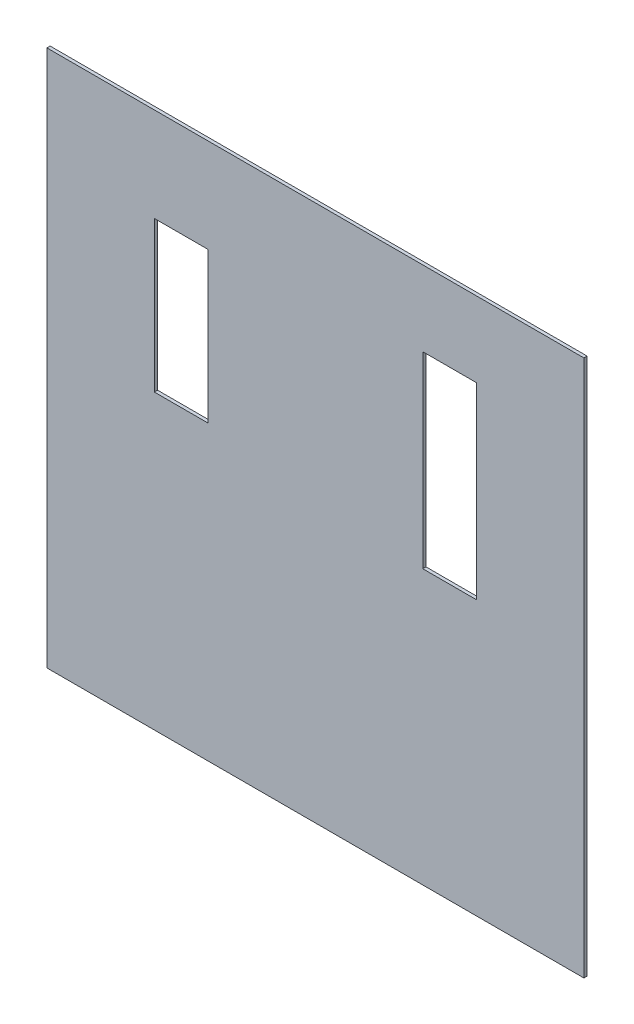
SolidWorks part; units mm, degrees
material "Custom Plastic"
ref_plane "Front Plane" through (0, 0, 0) normal (0, 0, 1) x (1, 0, 0)
ref_plane "Top Plane" through (0, 0, 0) normal (0, 1, 0) x (1, 0, 0)
ref_plane "Right Plane" through (0, 0, 0) normal (1, 0, 0) x (0, 0, -1)
sketch "Sketch1" plane through (0, 0, 0) normal (0, 0, 1) x (1, 0, 0)
  line L1 (0, 0) -> (25.4, 0)
  line L2 (0, 0) -> (0, 25.4)
  line L3 (0, 25.4) -> (25.4, 25.4)
  line L4 (25.4, 0) -> (25.4, 25.4)
  dimension "D1" = 25.4
  dimension "D2" = 25.4
extrude "Boss-Extrude1" add sketch "Sketch1" along normal blind 0.1524
sketch "Sketch2" plane through (0, 0, 0.1524) normal (0, 0, 1) x (1, 0, 0)
  line L0 (25.4, 25.4) -> (0, 25.4) construction
  line L1 (5.08, 20.955) -> (7.62, 20.955)
  line L2 (5.08, 20.955) -> (5.08, 13.843)
  line L3 (5.08, 13.843) -> (7.62, 13.843)
  line L4 (7.62, 20.955) -> (7.62, 13.843)
  line L5 (17.78, 21.844) -> (20.32, 21.844)
  line L6 (17.78, 21.844) -> (17.78, 12.954)
  line L7 (17.78, 12.954) -> (20.32, 12.954)
  line L8 (20.32, 21.844) -> (20.32, 12.954)
  point P10 (6.35, 20.955)
  point P11 (12.7, 25.4)
  point P12 (6.35, 13.843)
  point P13 (19.05, 12.954)
  dimension "D1" = 2.54
  dimension "D2" = 2.54
  dimension "D3" = 8.89
  dimension "D4" = 7.112
  dimension "D5" = 4.445
  dimension "D6" = 3.556
  dimension "D7" = 6.35
  dimension "D8" = 12.7
extrude "Cut-Extrude1" cut sketch "Sketch2" against normal through all
